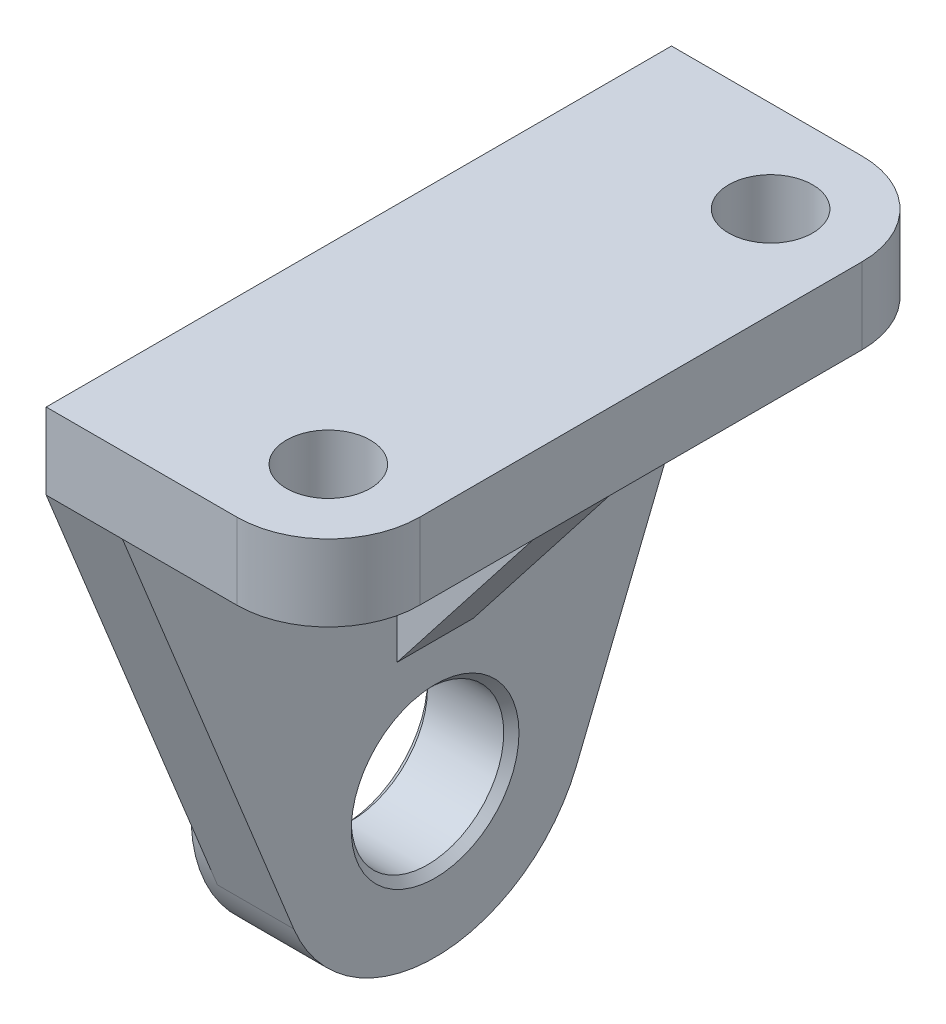
SolidWorks part; units mm, degrees
material "6063-T6"
ref_plane "Plan de face" through (0, 0, 0) normal (0, 0, 1) x (1, 0, 0)
ref_plane "Plan de dessus" through (0, 0, 0) normal (0, 1, 0) x (1, 0, 0)
ref_plane "Plan de droite" through (0, 0, 0) normal (1, 0, 0) x (0, 0, -1)
sketch "Esquisse1" plane through (0, 0, 0) normal (1, 0, 0) x (0, 0, -1)
  line L0 (-41, 58) -> (41, 58)
  line L1 (41, 58) -> (41, 48)
  line L2 (41, 48) -> (18.5395, -7.5025)
  line L3 (-41, 58) -> (-41, 48)
  line L4 (-41, 48) -> (-18.5395, -7.5025)
  arc A0 (-18.5395, -7.5025) -> (18.5395, -7.5025) centre (0, 0) ccw
  point P4 (0, 58)
  dimension "D1" = 20
  dimension "D2" = 82
  dimension "D3" = 10
  dimension "D4" = 48
extrude "Extrusion1" add sketch "Esquisse1" against normal blind 10
sketch "Esquisse2" plane through (0, 0, 0) normal (1, 0, 0) x (0, 0, -1)
  circle A0 centre (0, 0) radius 20
  dimension "D1" = 40
extrude "Extrusion2" add sketch "Esquisse2" against normal blind 12
sketch "Esquisse3" plane through (-10, 0, 0) normal (-1, 0, 0) x (0, 0, 1)
  line L1 (-41, 58) -> (41, 58)
  line L2 (-41, 58) -> (-41, 48)
  line L3 (-41, 48) -> (41, 48)
  line L4 (41, 58) -> (41, 48)
extrude "Extrusion3" add sketch "Esquisse3" against normal blind 37
fillet "Congé1" radius 12 2 edges at (27, 53, 41) (27, 53, -41)
hole_wizard "Chambrage pour vis à tête cylindrique à 6 pans creux (ou vis CHC) M41" positions "Esquisse5" profile "Esquisse4" counterbore size "M4" standard "Ansi Metric" end condition through all
sketch "Esquisse5" plane through (0, 48, 0) normal (0, -1, 0) x (1, 0, 0)
  arc A0 (27, 29) -> (15, 41) centre (15, 29) ccw construction
  point P0 (15, 29)
  point P5 (15, -29)
sketch "Esquisse4" plane through (15, 48, 29) normal (1, 0, 0) x (0, 0, -1)
  line L0 (0, 0) -> (0, 10)
  line L1 (0, 10) -> (5.5, 10)
  line L3 (5.5, 10) -> (5.5, 1)
  line L4 (5.5, 1) -> (11, 1)
  line L5 (11, 1) -> (11, 0)
  line L7 (11, 0) -> (0, 0)
  line L11 (0, -6.35) -> (0, 107.95) construction
  dimension "Diamètre du perçage jusqu'au prochain" = 11
  dimension "Profondeur du perçage jusqu'au prochain" = 10
  dimension "Diamètre du chambrage" = 22
  dimension "Profondeur du chambrage" = 1
hole_wizard "Dégagement M1.61" positions "Esquisse7" profile "Esquisse8" hole size "M1.6" standard "Ansi Métrique" end condition through all
sketch "Esquisse7" plane through (-12, 0, 0) normal (-1, 0, 0) x (0, 0, 1)
  point P0 (0, 0)
sketch "Esquisse8" plane through (-12, 0, 0) normal (0, 1, 0) x (0, 0, 1)
  line L0 (0, 0) -> (0, 39)
  line L1 (0, 39) -> (10, 39)
  line L2 (10, 39) -> (10, 0)
  line L5 (10, 0) -> (0, 0)
  line L11 (0, -6.35) -> (0, 107.95) construction
  dimension "Diamètre du perçage jusqu'au prochain" = 20
  dimension "Profondeur du perçage jusqu'au prochain" = 39
sketch "Esquisse9" plane through (0, 0, 0) normal (0, 0, 1) x (1, 0, 0)
  line L0 (25, 48) -> (0, 16)
  line L1 (15, 48) -> (27, 48) construction
  line L2 (0, 48) -> (0, -7.5025) construction
  dimension "D1" = 25
  dimension "D2" = 32
rib "Nervure1" sketch "Esquisse9" sketch "Esquisse9" thickness 10 extrusion direction parallel to sketch draft on no parameters "D1"=10
chamfer "Chanfrein1" distance 1 angle 45 2 edges at (-12, 0, 10) (0, 0, -10)
